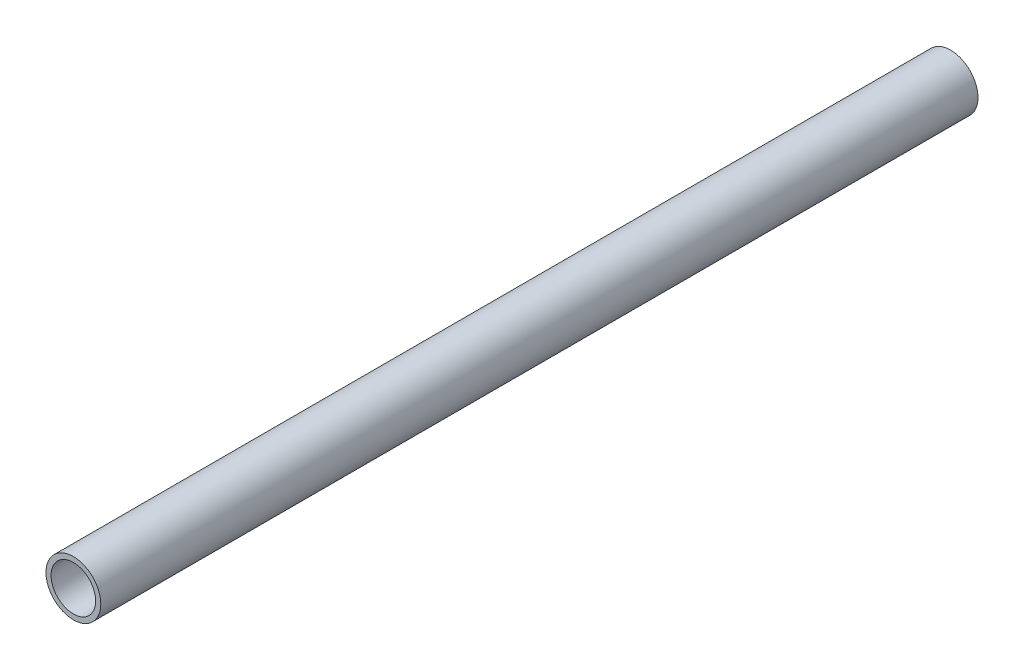
SolidWorks part; units mm, degrees
ref_plane "Front Plane" through (0, 0, 0) normal (0, 0, 1) x (1, 0, 0)
ref_plane "Top Plane" through (0, 0, 0) normal (0, 1, 0) x (1, 0, 0)
ref_plane "Right Plane" through (0, 0, 0) normal (1, 0, 0) x (0, 0, -1)
sketch "Sketch1" plane through (0, 0, 0) normal (0, 0, 1) x (1, 0, 0)
  line L0 (4.7625, 0) -> (3.8735, 0) construction
  line L1 (-4.7625, 0) -> (4.7625, 0) construction
  dimension "OD" = 9.525
  dimension "Wall Thickness" = 0.889
sketch "Sketch2" plane through (0, 0, 0) normal (1, 0, 0) x (0, 0, -1)
  line L0 (76.2, 0) -> (-76.2, 0)
  point P4 (0, 0)
  dimension "Length" = 152.4
sketch "Sketch3" plane through (0, 0, 0) normal (0, 0, 1) x (1, 0, 0)
  circle A0 centre (0, 0) radius 4.7625
  circle A1 centre (0, 0) radius 3.8735
extrude "Boss-Extrude1" add sketch "Sketch3" along normal up to vertex (76.2 mm away) and the other way up to vertex (76.2 mm away) up to point (0, 0, 76.2) other way up to point (0, 0, -76.2)
